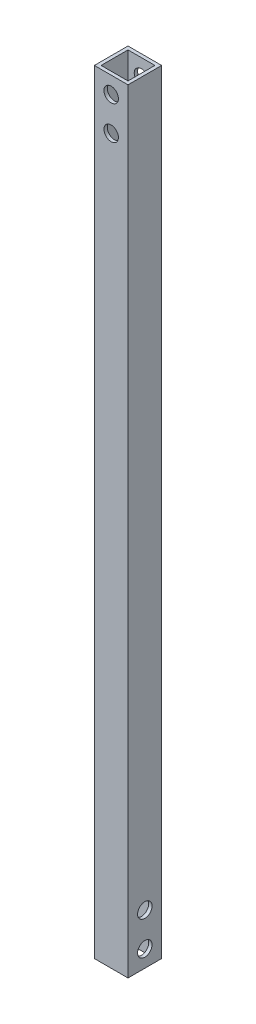
SolidWorks part; units mm, degrees
material "5052-H34"
ref_plane "正面" through (0, 0, 0) normal (0, 0, 1) x (1, 0, 0)
ref_plane "平面" through (0, 0, 0) normal (0, 1, 0) x (1, 0, 0)
ref_plane "右側面" through (0, 0, 0) normal (1, 0, 0) x (0, 0, -1)
sketch "ｽｹｯﾁ1" plane through (0, 0, 0) normal (0, 1, 0) x (1, 0, 0)
  line L1 (-5, 5) -> (5, 5)
  line L2 (-5, 5) -> (-5, -5)
  line L3 (-5, -5) -> (5, -5)
  line L4 (5, 5) -> (5, -5)
  line L5 (-5, 5) -> (5, -5) construction
  line L6 (-5, -5) -> (5, 5) construction
  point P0 (0, 0)
  dimension "D1" = 10
  dimension "D2" = 10
extrude "押し出し-薄板1" add sketch "ｽｹｯﾁ1" along normal blind 230 thin
sketch "ｽｹｯﾁ2" plane through (0, 0, 5) normal (0, 0, -1) x (-1, 0, 0)
  line L0 (0, 230) -> (0, 215) construction
  line L2 (-5, 230) -> (5, 230) construction
  circle A0 centre (0, 215) radius 2.15
  circle A1 centre (0, 225) radius 2.15
  dimension "D1" = 4.3
  dimension "D2" = 5
  dimension "D3" = 15
extrude "ｶｯﾄ - 押し出し1" cut sketch "ｽｹｯﾁ2" along normal through all
sketch "ｽｹｯﾁ3" plane through (5, 0, 0) normal (1, 0, 0) x (0, 0, -1)
  line L0 (0, 0) -> (0, 15) construction
  circle A0 centre (0, 15) radius 2.15
  circle A1 centre (0, 5) radius 2.15
  dimension "D2" = 4.3
  dimension "D1" = 15
  dimension "D3" = 5
extrude "ｶｯﾄ - 押し出し2" cut sketch "ｽｹｯﾁ3" against normal through all
